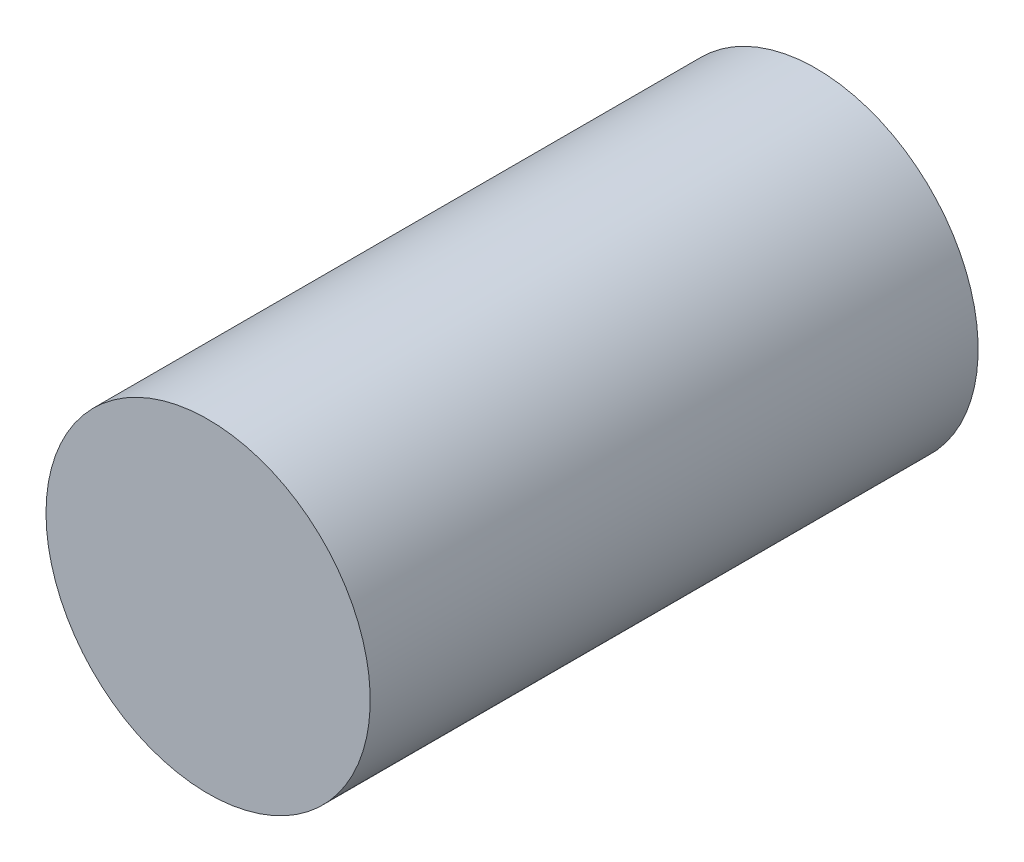
SolidWorks part; units mm, degrees
ref_plane "Front Plane" through (0, 0, 0) normal (0, 0, 1) x (1, 0, 0)
ref_plane "Top Plane" through (0, 0, 0) normal (0, 1, 0) x (1, 0, 0)
ref_plane "Right Plane" through (0, 0, 0) normal (1, 0, 0) x (0, 0, -1)
sketch "Sketch1" plane through (0, 0, 0) normal (0, 0, 1) x (1, 0, 0)
  circle A2 centre (0, 0) radius 3
  dimension "D1" = 6
extrude "Boss-Extrude1" add sketch "Sketch1" along normal blind 11.25
equation "\"shaft inner diameter\"= 15mm "
equation "\"shaft outer diameter\"= 20mm "
equation "\"column angle\" = 45deg "
equation "\"keyway_height\" = 1.39mm "
equation "\"keyway_width\" = 2.78mm "
equation "\"keyway_length\" = 30mm "
equation "\"steering column length\" = 555mm "
equation "\"steering wheel bolt width\" = 6mm "
equation "\"steering wheel bolt length\" = 40mm "
equation "\"bushing length\" = 40mm "
equation "\"bushing thickness\" = 3mm "
equation "\"u_joint clearance\" = 30mm "
equation "\"u_joint thickness\" = 7.5mm "
equation "\"horizontal shaft length\" = 90mm "
equation "\"short_bearing_outer_width\" = 10mm "
equation "\"column bushing diameter\" = \"primary shaft small diameter\" + 4 "
equation "\"column bushing distance\" = \"steering column length\"/4 "
equation "\"pinion width\" = 26.5mm "
equation "\"number of teeth\" = 18mm "
equation "\"D1@Boss-Extrude1\"=(\"u_joint thickness\"*0.75)*2"
equation "\"wheel base\" = 1561mm "
equation "\"track\" = 1354mm "
equation "\"turning radius\" = 2000mm "
equation "\"turn to lock\" = 0.75mm "
equation "\"steering arm length\" = 100mm "
equation "\"primary shaft small diameter\" = 16mm "
equation "\"primary shaft large diameter\" = 24mm "
equation "\"secondary shaft small diameter\" = 16mm "
equation "\"secondary shaft large diameter\" = 25mm "
equation "\"pin hole diameter\" = 10mm "
equation "\"rack hole to hole\" = 500mm "
equation "\"rack length\" = \"rack hole to hole\" + \"pin hole diameter\"*2 "
equation "\"max turning angle\" = atn(\"wheel base\" / (\"turning radius\" - 0.5 * \"track\")) "
equation "\"max travel\" = 2 * \"steering arm length\" * sin(0.5 * \"max turning angle\") "
equation "\"pitch diameter\" = \"max travel\"/(pi * \"turn to lock\") "
equation "\"pressure angle\" = 20deg "
equation "\"module\" = \"pitch diameter\" / \"number of teeth\" "
equation "\"tie rod length\" = 305mm "
equation "\"tie rod inner diameter\" = 6.6mm "
equation "\"tie rod outer diameter\" = 8.1mm "
